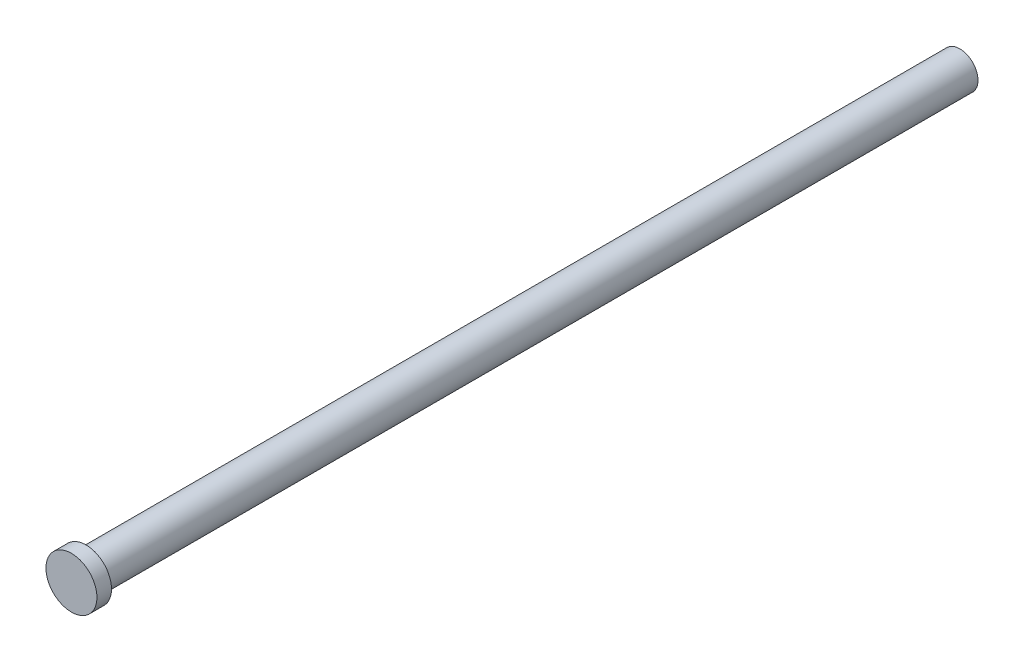
SolidWorks part; units mm, degrees
ref_plane "Front Plane" through (0, 0, 0) normal (0, 0, 1) x (1, 0, 0)
ref_plane "Top Plane" through (0, 0, 0) normal (0, 1, 0) x (1, 0, 0)
ref_plane "Right Plane" through (0, 0, 0) normal (1, 0, 0) x (0, 0, -1)
sketch "Sketch1" plane through (0, 0, 0) normal (0, 0, 1) x (1, 0, 0)
  circle A0 centre (0, 0) radius 12.5
  dimension "D1" = 25
extrude "Boss-Extrude1" add sketch "Sketch1" along normal blind 600
sketch "Sketch2" plane through (0, 0, 600) normal (0, 0, 1) x (1, 0, 0)
  circle A0 centre (0, 0) radius 17.5
  dimension "D1" = 35
extrude "Boss-Extrude2" add sketch "Sketch2" along normal blind 10
